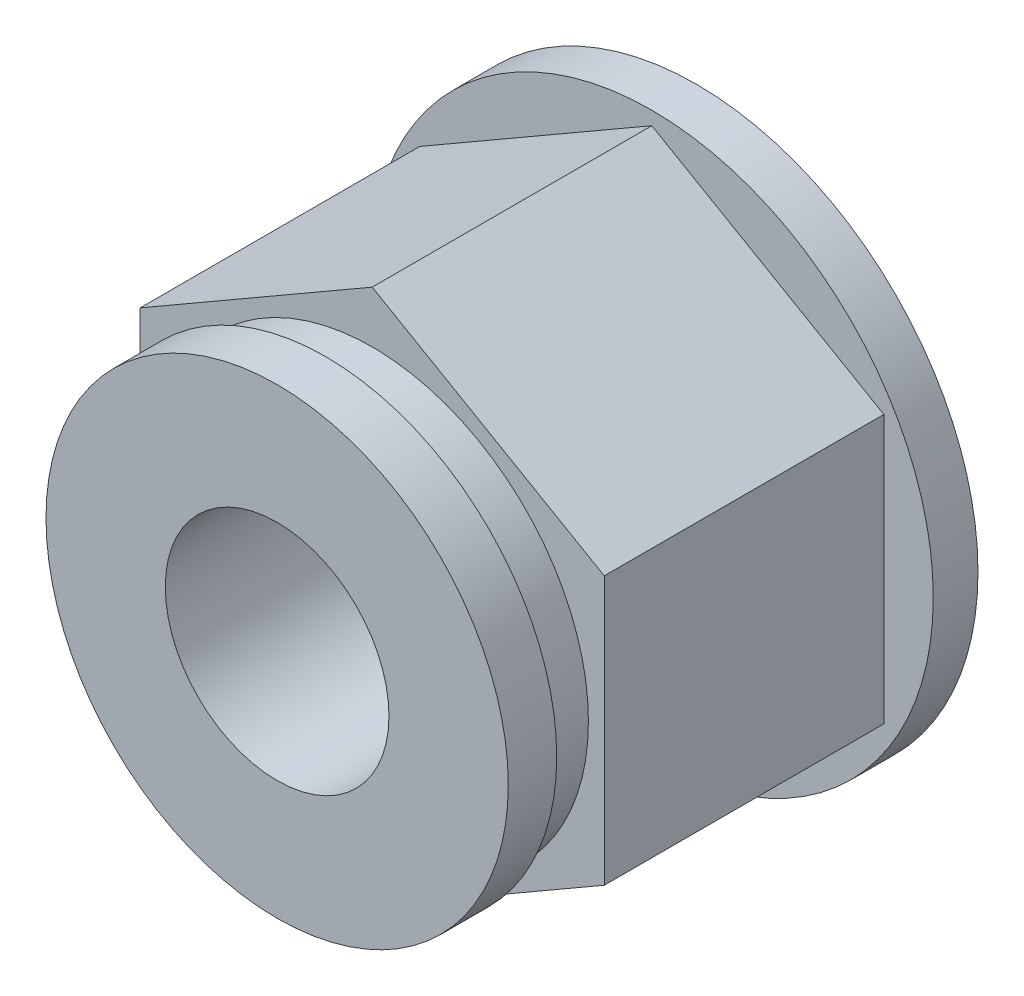
SolidWorks part; units mm, degrees
ref_plane "Plan de face" through (0, 0, 0) normal (0, 0, 1) x (1, 0, 0)
ref_plane "Plan de dessus" through (0, 0, 0) normal (0, 1, 0) x (1, 0, 0)
ref_plane "Plan de droite" through (0, 0, 0) normal (1, 0, 0) x (0, 0, -1)
sketch "Esquisse1" plane through (0, 0, 0) normal (0, 0, 1) x (1, 0, 0)
  circle A0 centre (0, 0) radius 7.55
  dimension "D1" = 15.1
extrude "Boss.-Extru.1" add sketch "Esquisse1" along normal blind 1.2
sketch "Esquisse2" plane through (0, 0, 1.2) normal (0, 0, 1) x (1, 0, 0)
  line L1 (6.225, -3.594) -> (6.225, 3.594)
  line L2 (6.225, 3.594) -> (0, 7.188)
  line L3 (0, 7.188) -> (-6.225, 3.594)
  line L4 (-6.225, 3.594) -> (-6.225, -3.594)
  line L5 (-6.225, -3.594) -> (0, -7.188)
  line L6 (0, -7.188) -> (6.225, -3.594)
  circle A0 centre (0, 0) radius 6.225 construction
  dimension "D1" = 12.45
extrude "Boss.-Extru.2" add sketch "Esquisse2" along normal blind 7.5
sketch "Esquisse3" plane through (0, 0, 8.7) normal (0, 0, 1) x (1, 0, 0)
  circle A0 centre (0, 0) radius 5.8
  dimension "D1" = 11.6
extrude "Boss.-Extru.3" add sketch "Esquisse3" along normal blind 1.25
sketch "Esquisse4" plane through (0, 0, 9.95) normal (0, 0, 1) x (1, 0, 0)
  circle A0 centre (0, 0) radius 6.2
  dimension "D1" = 12.4
extrude "Boss.-Extru.4" add sketch "Esquisse4" along normal blind 1.3
sketch "Esquisse5" plane through (0, 0, 11.25) normal (0, 0, 1) x (1, 0, 0)
  circle A0 centre (0, 0) radius 3
  dimension "D1" = 6
extrude "Enlèv. mat.-Extru.1" cut sketch "Esquisse5" against normal through all
